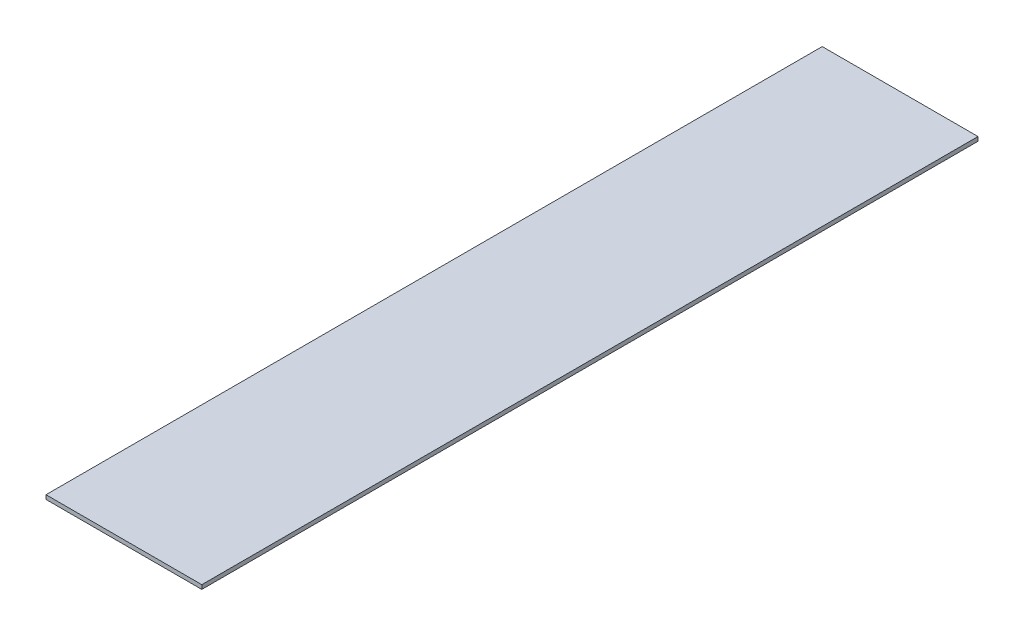
SolidWorks part; units mm, degrees
material "CA"
ref_plane "Front Plane" through (0, 0, 0) normal (0, 0, 1) x (1, 0, 0)
ref_plane "Top Plane" through (0, 0, 0) normal (0, 1, 0) x (1, 0, 0)
ref_plane "Right Plane" through (0, 0, 0) normal (1, 0, 0) x (0, 0, -1)
sketch "Sketch1" plane through (0, 0, 0) normal (0, 1, 0) x (1, 0, 0)
  line L1 (0, 0) -> (113, 0)
  line L2 (0, 0) -> (0, 563)
  line L3 (0, 563) -> (113, 563)
  line L4 (113, 0) -> (113, 563)
  dimension "D1" = 563
  dimension "D2" = 113
extrude "Boss-Extrude1" add sketch "Sketch1" along normal blind 3
